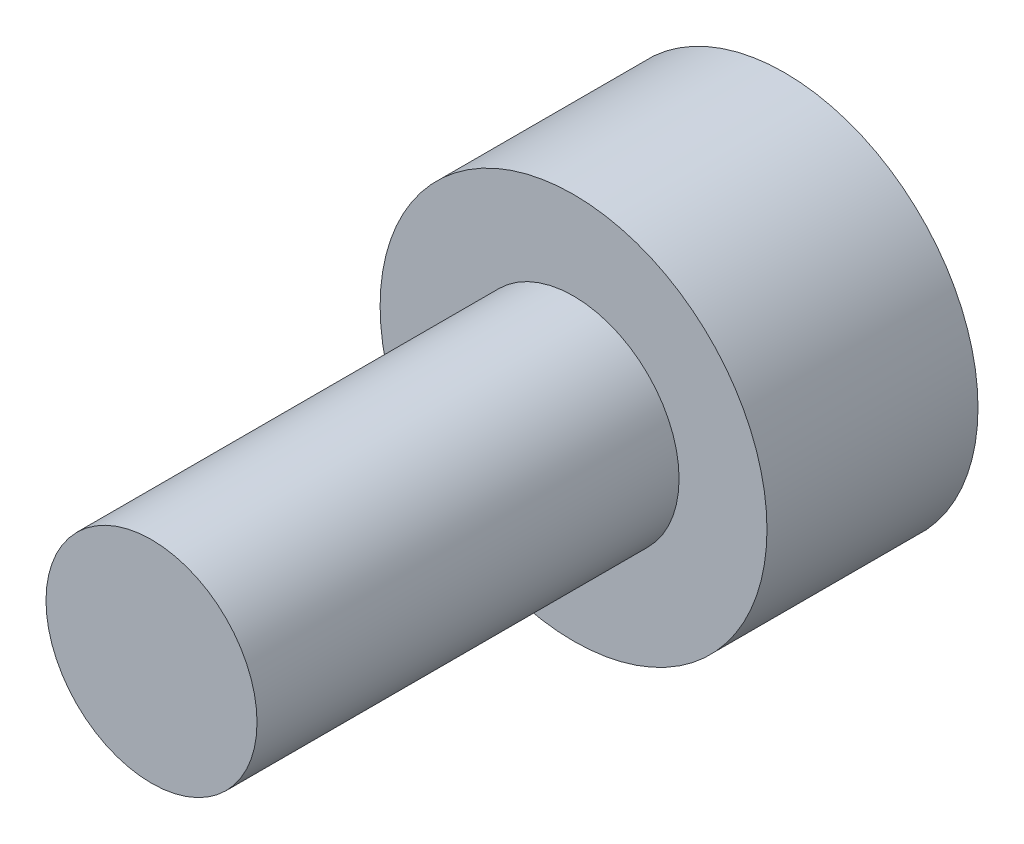
SolidWorks part; units mm, degrees
material "Acero aleado"
ref_plane "Alzado" through (0, 0, 0) normal (0, 0, 1) x (1, 0, 0)
ref_plane "Planta" through (0, 0, 0) normal (0, 1, 0) x (1, 0, 0)
ref_plane "Vista lateral" through (0, 0, 0) normal (1, 0, 0) x (0, 0, -1)
sketch "Croquis1" plane through (0, 0, 0) normal (0, 0, 1) x (1, 0, 0)
  circle A0 centre (0, 0) radius 2.75
  dimension "D1" = 5.5
extrude "Cabeza" add sketch "Croquis1" along normal blind 3 from offset 3
sketch "Croquis2" plane through (0, 0, 0) normal (0, 0, 1) x (1, 0, 0)
  circle A0 centre (0, 0) radius 1.5
  dimension "D1" = 3
extrude "Cuerpo" add sketch "Croquis2" along normal blind 6
sketch "Croquis3" plane through (0, 0, 0) normal (0, 0, 1) x (1, 0, 0)
  line L0 (1.4434, 0) -> (0.7217, 1.25)
  line L1 (0.7217, 1.25) -> (-0.7217, 1.25)
  line L2 (-0.7217, 1.25) -> (-1.4434, 0)
  line L3 (-1.4434, 0) -> (-0.7217, -1.25)
  line L4 (-0.7217, -1.25) -> (0.7217, -1.25)
  line L5 (0.7217, -1.25) -> (1.4434, 0)
  dimension "D1" = 1.4434
  dimension "D2" = 0.7217
  dimension "D3" = 1.25
  dimension "D4" = 0.7217
  dimension "D5" = 1.25
  dimension "D6" = 1.4434
  dimension "D7" = 0.7217
  dimension "D8" = 1.25
  dimension "D9" = 0.7217
  dimension "D10" = 1.25
extrude "Hexagono_interior" cut sketch "Croquis3" along normal blind 1.3 from offset 3
